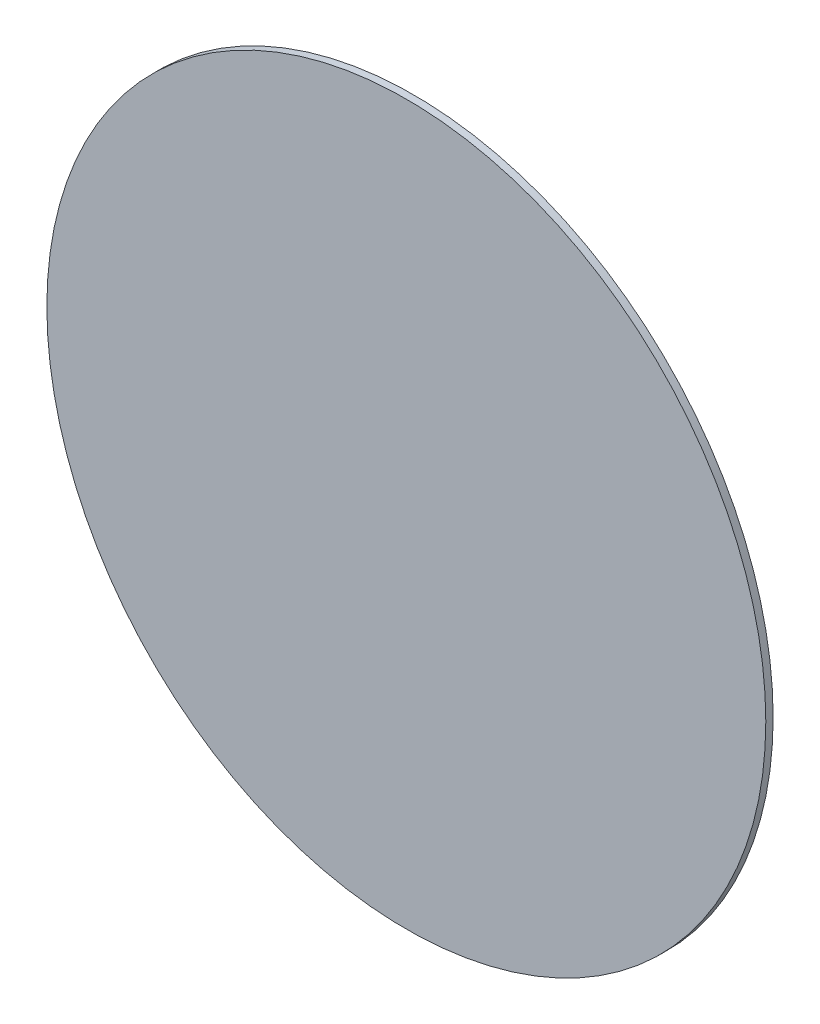
SolidWorks part; units mm, degrees
material "Silicon"
ref_plane "Front Plane" through (0, 0, 0) normal (0, 0, 1) x (1, 0, 0)
ref_plane "Top Plane" through (0, 0, 0) normal (0, 1, 0) x (1, 0, 0)
ref_plane "Right Plane" through (0, 0, 0) normal (1, 0, 0) x (0, 0, -1)
sketch "Sketch1" plane through (0, 0, 0) normal (0, 0, 1) x (1, 0, 0)
  circle A1 centre (0, 0) radius 147
extrude "Boss-Extrude1" add sketch "Sketch1" along normal blind 3
